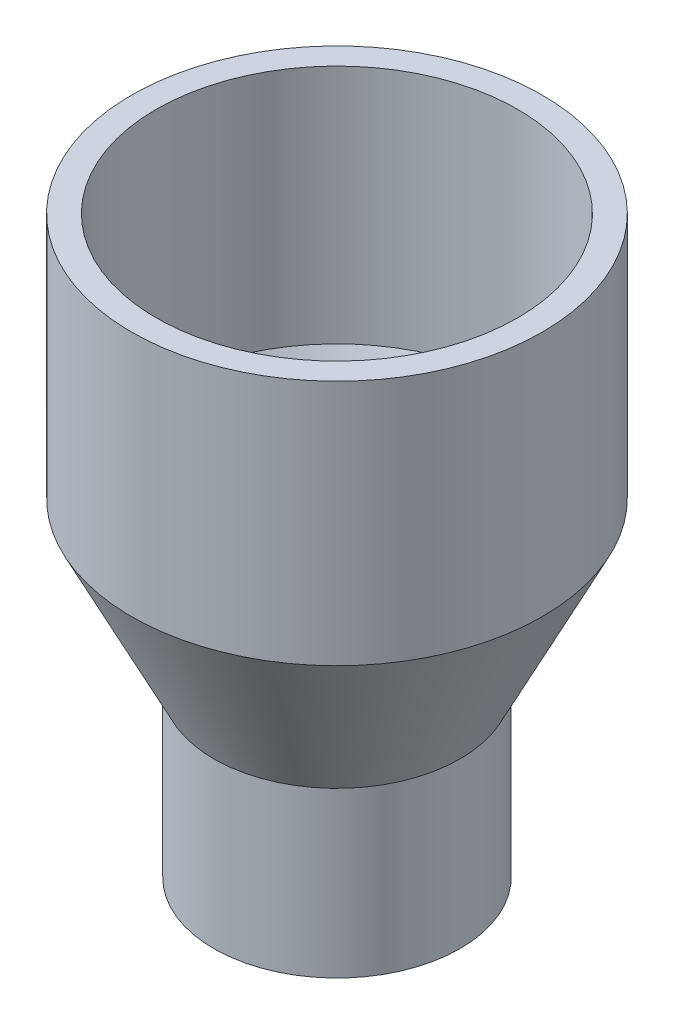
SolidWorks part; units mm, degrees
ref_plane "Front Plane" through (0, 0, 0) normal (0, 0, 1) x (1, 0, 0)
ref_plane "Top Plane" through (0, 0, 0) normal (0, 1, 0) x (1, 0, 0)
ref_plane "Right Plane" through (0, 0, 0) normal (1, 0, 0) x (0, 0, -1)
sketch "Sketch1" plane through (0, 0, 0) normal (0, 0, 1) x (1, 0, 0)
  line L0 (0, -17.5) -> (0, 17.5) construction
  line L1 (12.5, 17.5) -> (12.5, 2.5)
  line L2 (12.5, 2.5) -> (7.5, -7.5)
  line L3 (7.5, -7.5) -> (7.5, -17.5)
  line L4 (11, 17.5) -> (11, 2.8541)
  line L5 (11, 2.8541) -> (6, -7.1459)
  line L6 (6, -7.1459) -> (6, -17.5)
  line L7 (7.5, -7.5) -> (7.5, -60.9949) construction
  line L8 (6, -7.1459) -> (6, -60.9949) construction
  line L9 (7.5, -17.5) -> (6, -17.5)
  line L10 (11, 17.5) -> (12.5, 17.5)
  point P4 (0, 0)
  dimension "D2" = 12.5
  dimension "D3" = 35
  dimension "D4" = 15
  dimension "D5" = 15
  dimension "D6" = 10
  dimension "D1" = 1.5
revolve "Revolve1" add sketch "Sketch1" angle 360 about L0
